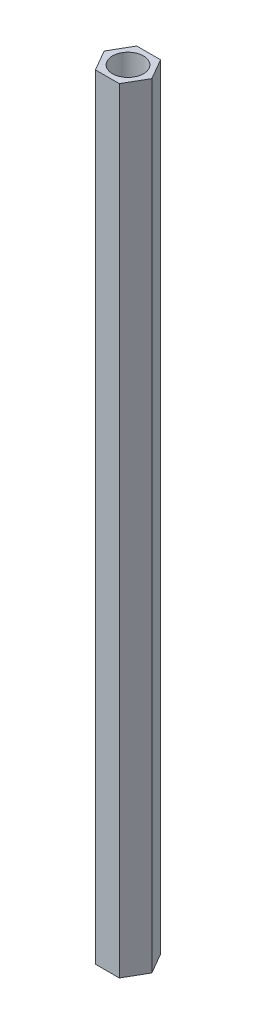
SolidWorks part; units mm, degrees
ref_plane "Front Plane" through (0, 0, 0) normal (0, 0, 1) x (1, 0, 0)
ref_plane "Top Plane" through (0, 0, 0) normal (0, 1, 0) x (1, 0, 0)
ref_plane "Right Plane" through (0, 0, 0) normal (1, 0, 0) x (0, 0, -1)
sketch "草图1" plane through (0, 0, 0) normal (0, 1, 0) x (1, 0, 0)
  line L1 (2.3094, 0) -> (1.1547, 2)
  line L2 (1.1547, 2) -> (-1.1547, 2)
  line L3 (-1.1547, 2) -> (-2.3094, 0)
  line L4 (-2.3094, 0) -> (-1.1547, -2)
  line L5 (-1.1547, -2) -> (1.1547, -2)
  line L6 (1.1547, -2) -> (2.3094, 0)
  circle A0 centre (0, 0) radius 2 construction
  dimension "D1" = 4
extrude "凸台-拉伸1" add sketch "草图1" along normal blind 75
sketch "草图2" plane through (0, 75, 0) normal (0, 1, 0) x (1, 0, 0)
  circle A0 centre (0, 0) radius 1.5
  dimension "D1" = 3
extrude "切除-拉伸1" cut sketch "草图2" against normal through all
